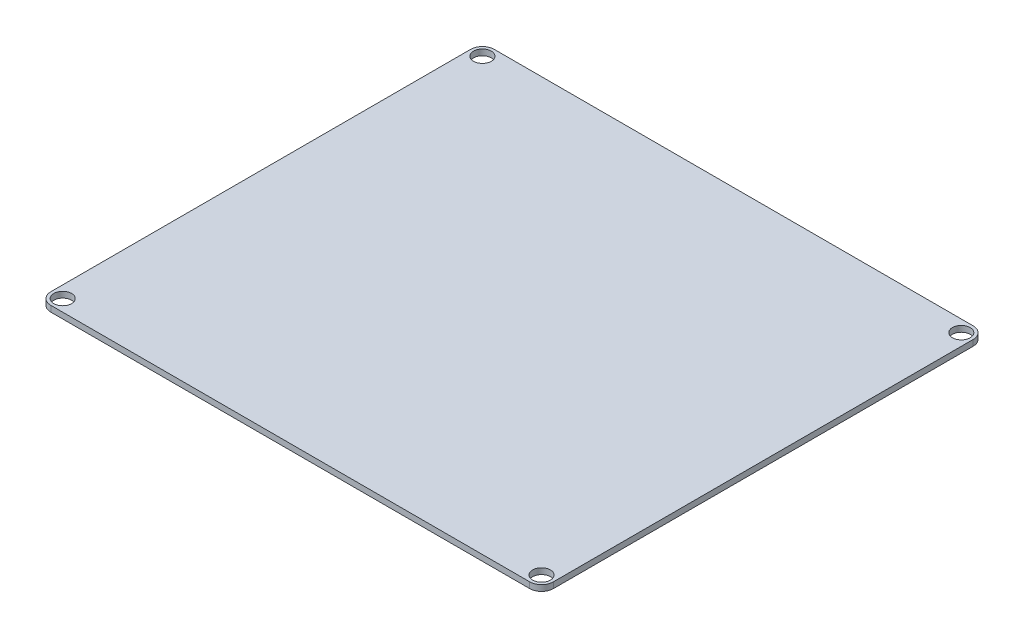
SolidWorks part; units mm, degrees
ref_plane "Front Plane" through (0, 0, 0) normal (0, 0, 1) x (1, 0, 0)
ref_plane "Top Plane" through (0, 0, 0) normal (0, 1, 0) x (1, 0, 0)
ref_plane "Right Plane" through (0, 0, 0) normal (1, 0, 0) x (0, 0, -1)
sketch "Sketch1" plane through (0, 0, 0) normal (0, 1, 0) x (1, 0, 0)
  line L1 (-40.5, -37.5) -> (40.5, -37.5)
  line L2 (-42.5, -35.5) -> (-42.5, 35.5)
  line L3 (-40.5, 37.5) -> (40.5, 37.5)
  line L4 (42.5, -35.5) -> (42.5, 35.5)
  line L5 (-42.5, -37.5) -> (42.5, 37.5) construction
  line L6 (-42.5, 37.5) -> (42.5, -37.5) construction
  arc A0 (-40.5, -37.5) -> (-42.5, -35.5) centre (-40.5, -35.5) cw
  arc A1 (40.5, -37.5) -> (42.5, -35.5) centre (40.5, -35.5) ccw
  arc A2 (40.5, 37.5) -> (42.5, 35.5) centre (40.5, 35.5) cw
  arc A3 (-42.5, 35.5) -> (-40.5, 37.5) centre (-40.5, 35.5) cw
  circle A4 centre (-40.5, 35.5) radius 1.5
  circle A5 centre (40.5, 35.5) radius 1.5
  circle A6 centre (40.5, -35.5) radius 1.5
  circle A7 centre (-40.5, -35.5) radius 1.5
  point P0 (0, 0)
  dimension "D3" = 2
  dimension "D1" = 85
  dimension "D2" = 75
extrude "Boss-Extrude1" add sketch "Sketch1" along normal blind 1
